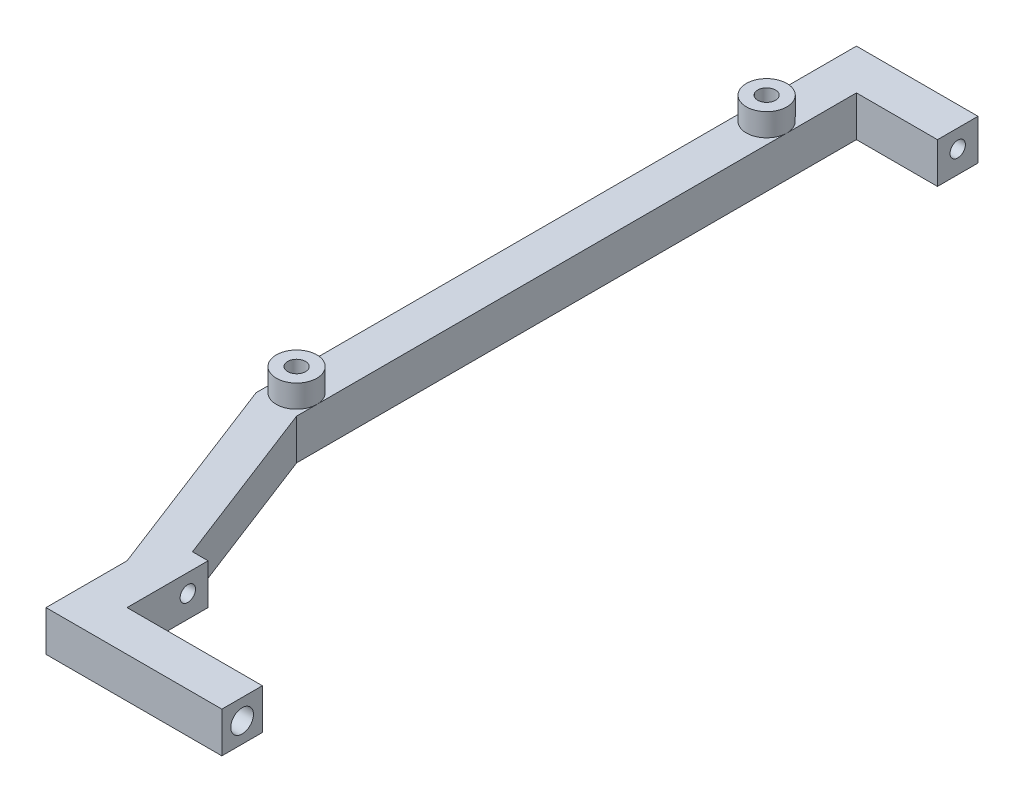
SolidWorks part; units mm, degrees
ref_plane "Front Plane" through (0, 0, 0) normal (0, 0, 1) x (1, 0, 0)
ref_plane "Top Plane" through (0, 0, 0) normal (0, 1, 0) x (1, 0, 0)
ref_plane "Right Plane" through (0, 0, 0) normal (1, 0, 0) x (0, 0, -1)
sketch "Sketch1" plane through (0, 0, 0) normal (0, 0, 1) x (1, 0, 0)
  line L1 (-2.5, 2.5) -> (2.5, 2.5)
  line L2 (-2.5, 2.5) -> (-2.5, -2.5)
  line L3 (-2.5, -2.5) -> (2.5, -2.5)
  line L4 (2.5, 2.5) -> (2.5, -2.5)
  line L5 (-2.5, 2.5) -> (2.5, -2.5) construction
  line L6 (-2.5, -2.5) -> (2.5, 2.5) construction
  point P0 (0, 0)
  dimension "D1" = 5
  dimension "D2" = 5
extrude "Boss-Extrude1" add sketch "Sketch1" along normal blind 74.08
sketch "Sketch2" plane through (0, 0, 0) normal (0, 0, -1) x (-1, 0, 0)
  circle A0 centre (0, 0) radius 1.4
  dimension "D1" = 2.8
extrude "Cut-Extrude1" cut sketch "Sketch2" against normal blind 10
sketch "Sketch3" plane through (2.5, 0, 0) normal (1, 0, 0) x (0, 0, -1)
  line L0 (-74.08, 2.5) -> (0, 2.5) construction
  line L1 (0, 2.5) -> (-5, 2.5)
  line L2 (0, 2.5) -> (0, -2.5)
  line L3 (0, -2.5) -> (-5, -2.5)
  line L4 (-5, 2.5) -> (-5, -2.5)
  line L5 (-74.08, -2.5) -> (0, -2.5) construction
  line L6 (0, -2.5) -> (0, 2.5) construction
  dimension "D1" = 5
  dimension "D2" = 0
extrude "Boss-Extrude2" add sketch "Sketch3" along normal blind 10
sketch "Sketch4" plane through (12.5, 0, 0) normal (1, 0, 0) x (0, 0, -1)
  line L0 (0, 2.5) -> (-5, -2) construction
  line L1 (-5, 2.5) -> (-5, -2.5) construction
  line L2 (-5, -2.5) -> (0, -2.5) construction
  circle A0 centre (-2.5, 0.25) radius 0.95
  dimension "D1" = 1.9
  dimension "D2" = 0.5
extrude "Cut-Extrude2" cut sketch "Sketch4" against normal blind 5
sketch "Sketch5" plane through (0, 2.5, 0) normal (0, 1, 0) x (1, 0, 0)
  line L0 (0, -74.08) -> (0, 0) construction
  line L1 (-2.5, -69.08) -> (2.5, -74.08) construction
  line L2 (2.5, -74.08) -> (2.5, -5) construction
  line L3 (12.5, 0) -> (-2.5, 0) construction
  circle A0 centre (0, -13.58) radius 2.5
  circle A1 centre (0, -71.58) radius 2.5
  circle A2 centre (0, -13.58) radius 1.1
  circle A3 centre (0, -71.58) radius 1.1
  dimension "D1" = 2.2
  dimension "D2" = 13.58
extrude "Boss-Extrude3" add sketch "Sketch5" along normal blind 2.8
sketch "Sketch6" plane through (12.5, 0, 0) normal (1, 0, 0) x (0, 0, -1)
  line L6 (-95, -2.5) -> (-95, 2.5)
  line L7 (-95, 2.5) -> (-100, 2.5)
  line L8 (-100, 2.5) -> (-100, -2.5)
  line L9 (-100, -2.5) -> (-95, -2.5)
  line L10 (0, -2.5) -> (0, 2.5)
  line L11 (0, 2.5) -> (-5, 2.5)
  line L12 (-5, 2.5) -> (-5, -2.5)
  line L13 (-5, -2.5) -> (0, -2.5)
  line L14 (0, -2.5) -> (0, 2.5) construction
  line L15 (0, 2.5) -> (-5, 2.5) construction
  line L16 (-5, 2.5) -> (-5, -2.5) construction
  line L17 (-5, -2.5) -> (0, -2.5) construction
  circle A0 centre (-2.5, 0.25) radius 0.95 construction
  circle A1 centre (-2.5, 0.25) radius 0.95 construction
  circle A2 centre (-97.5, 0.25) radius 0.95
  dimension "D1" = 0
  dimension "D2" = 2
extrude "Boss-Extrude4" add sketch "Sketch6" against normal blind 5 separate body
sketch "Sketch7" plane through (0, 2.5, 0) normal (0, 1, 0) x (1, 0, 0)
  line L0 (7.5, -100) -> (-2.5, -74.08)
  line L1 (-2.5, -74.08) -> (2.5, -74.08)
  line L2 (2.5, -74.08) -> (10.571, -95)
  line L5 (10.571, -95) -> (7.5, -95)
  line L6 (7.5, -95) -> (7.5, -100)
  line L7 (7.5, -95) -> (12.5, -95) construction
  line L8 (10.571, -95) -> (12.5, -100) construction
extrude "Boss-Extrude5" add sketch "Sketch7" against normal up to surface (5 mm away) from surface at 0 up to face at (10, -2.5, 97.5) starting at face at (0, 2.5, 42.58)
sketch "Sketch8" plane through (0, 0, 0) normal (0, 1, 0) x (1, 0, 0)
  line L0 (7.5, -100) -> (7.5, -110)
  line L1 (7.5, -110) -> (29.2, -110)
  line L2 (29.2, -110) -> (29.2, -105)
  line L3 (29.2, -105) -> (12.5, -105)
  line L4 (12.5, -105) -> (12.5, -100)
  line L5 (7.5, -100) -> (12.5, -100) construction
  line L6 (12.5, -95) -> (12.5, -100) construction
  line L7 (7.5, -100) -> (12.5, -100)
  dimension "D1" = 5
  dimension "D2" = 5
  dimension "D3" = 16.7
extrude "Boss-Extrude6" add sketch "Sketch8" against normal up to surface (5 mm away) from surface at 2.5 up to face at (6.8071, -2.5, 54.816) starting at face at (0, 2.5, 42.58)
sketch "Sketch9" plane through (29.2, 0, 0) normal (1, 0, 0) x (0, 0, -1)
  line L0 (-110, 2.5) -> (-105, -2.5) construction
  line L1 (-105, -2.5) -> (-105, 2.5) construction
  line L2 (-105, -2.5) -> (-110, -2.5) construction
  circle A0 centre (-107.5, 0) radius 1.4
  dimension "D2" = 2.8
  dimension "D1" = 0
extrude "Cut-Extrude3" cut sketch "Sketch9" against normal blind 10
